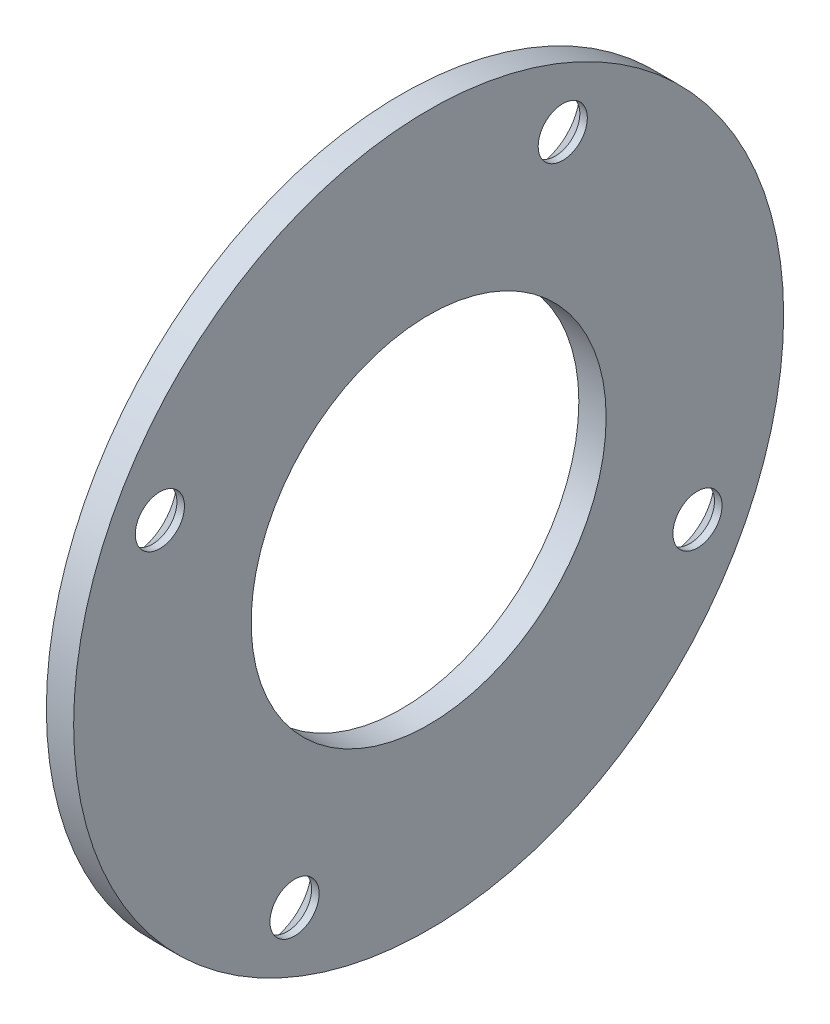
SolidWorks part; units mm, degrees
ref_plane "Спереди" through (0, 0, 0) normal (0, 0, 1) x (1, 0, 0)
ref_plane "Сверху" through (0, 0, 0) normal (0, 1, 0) x (1, 0, 0)
ref_plane "Справа" through (0, 0, 0) normal (1, 0, 0) x (0, 0, -1)
sketch "Эскиз1" plane through (0, 0, 0) normal (1, 0, 0) x (0, 0, -1)
  circle A0 centre (0, 0) radius 26
  circle A1 centre (0, 0) radius 13
  circle A2 centre (0, 0) radius 13 construction
  circle A3 centre (0, 0) radius 26 construction
extrude "Бобышка-Вытянуть1" add sketch "Эскиз1" along normal blind 2
hole_wizard "Зенковка для винта с полупотайной головкой M32" positions "Эскиз6" profile "Эскиз7" countersink size "M3" standard "DIN" end condition up to next
sketch "Эскиз6" plane through (0, 0, 0) normal (-1, 0, 0) x (0, 0, 1)
  circle A0 centre (19.686, 9.8215) radius 1.8 construction
  point P0 (19.686, 9.8215)
  point P5 (0, 0)
  point P8 (0, 0)
sketch "Эскиз7" plane through (0, 9.8215, 19.686) normal (0, 1, 0) x (0, 0, 1)
  line L0 (0, 0) -> (0, 2)
  line L1 (0, 2) -> (1.8, 2)
  line L2 (1.8, 2) -> (1.8, 1.45)
  line L3 (1.8, 1.45) -> (3.25, 0)
  line L5 (3.25, 0) -> (0, 0)
  line L6 (-1.8, 1.45) -> (-3.25, 0) construction
  line L11 (0, -6.35) -> (0, 107.95) construction
  dimension "Диаметр сквозного отверстия" = 3.6
  dimension "Глубина сквозного отверстия" = 2
  dimension "Диаметр передней зенковки" = 6.5
  dimension "Угол передней зенковки" = 90
pattern_circular "Круговой массив1" count 4 over 360 about axis through (0, 0, 0) along (1, 0, 0) of "Зенковка для винта с полупотайной головкой M32"
